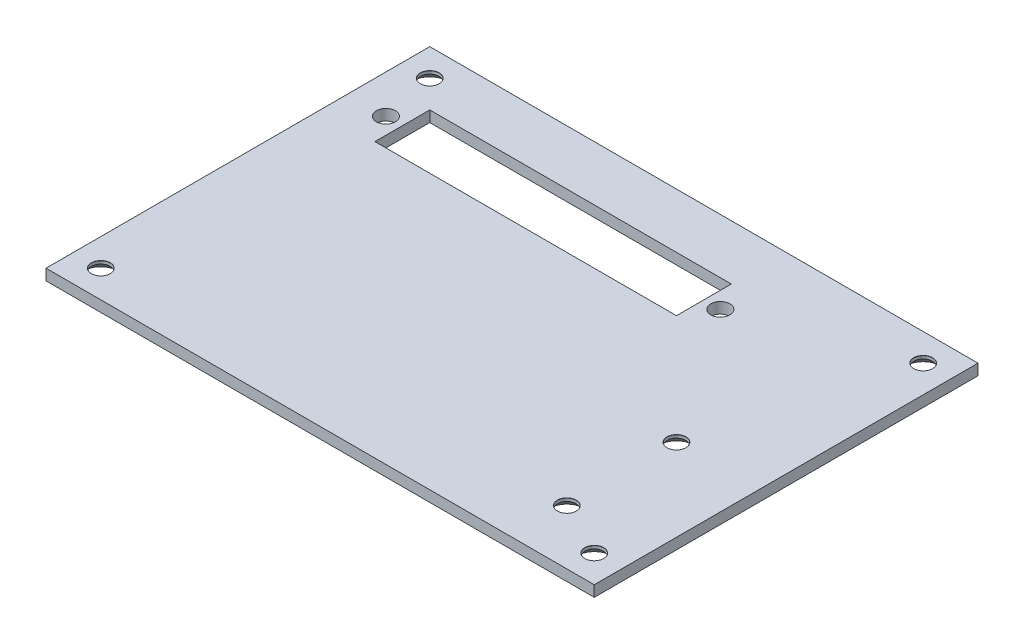
SolidWorks part; units mm, degrees
ref_plane "Ebene vorne" through (0, 0, 0) normal (0, 0, 1) x (1, 0, 0)
ref_plane "Ebene oben" through (0, 0, 0) normal (0, 1, 0) x (1, 0, 0)
ref_plane "Ebene rechts" through (0, 0, 0) normal (1, 0, 0) x (0, 0, -1)
sketch "Skizze1" plane through (0, 0, 0) normal (0, 1, 0) x (1, 0, 0)
  line L1 (0, 0) -> (100, 0)
  line L2 (0, 0) -> (0, 70)
  line L3 (0, 70) -> (100, 70)
  line L4 (100, 0) -> (100, 70)
  line L5 (10, 60) -> (65, 60)
  line L6 (10, 60) -> (10, 50)
  line L7 (10, 50) -> (65, 50)
  line L8 (65, 60) -> (65, 50)
  dimension "D1" = 100
  dimension "D2" = 70
  dimension "D3" = 10
  dimension "D4" = 55
  dimension "D5" = 10
  dimension "D6" = 10
extrude "Aufsatz-Linear austragen1" add sketch "Skizze1" along normal blind 2
hole_wizard "Ø3.5 (3.5) Durchmesser Bohrung1" positions "Skizze4" profile "Skizze5" hole size "Ø3.5" standard "DIN" end condition up to next
sketch "Skizze4" plane through (0, 2, 0) normal (0, 1, 0) x (1, 0, 0)
  line L1 (10, 60) -> (10, 50) construction
  line L2 (65, 50) -> (65, 60) construction
  line L3 (100, 70) -> (0, 70) construction
  point P0 (7, 55)
  point P2 (68, 55)
  dimension "D1" = 15
  dimension "D2" = 3
  dimension "D3" = 3
  dimension "D4" = 15
sketch "Skizze5" plane through (7, 2, -55) normal (1, 0, 0) x (0, 0, 1)
  line L0 (0, 0) -> (0, 2)
  line L1 (0, 2) -> (1.75, 2)
  line L2 (1.75, 2) -> (1.75, 0)
  line L5 (1.75, 0) -> (0, 0)
  line L11 (0, -6.35) -> (0, 107.95) construction
  dimension "Bohrerdurchmesser" = 3.5
  dimension "Bohrungstiefe" = 2
hole_wizard "Formsenkung für M3 Linsensenkschraube mit Schlitz1" positions "Skizze6" profile "Skizze7" countersink size "M3" standard "DIN" end condition up to next
sketch "Skizze6" plane through (0, 0, 0) normal (0, -1, 0) x (-1, 0, 0)
  line L0 (0, 0) -> (-100, 0) construction
  line L1 (0, 70) -> (0, 0) construction
  line L2 (-100, 0) -> (-100, 70) construction
  line L3 (-100, 70) -> (0, 70) construction
  point P0 (-5, 5)
  point P2 (-95, 5)
  point P4 (-95, 65)
  point P6 (-5, 65)
  dimension "D1" = 5
  dimension "D2" = 5
  dimension "D3" = 5
  dimension "D4" = 5
  dimension "D5" = 5
  dimension "D6" = 5
  dimension "D7" = 5
  dimension "D8" = 5
sketch "Skizze7" plane through (5, 0, -5) normal (1, 0, 0) x (0, 0, -1)
  line L0 (0, 0) -> (0, 2)
  line L1 (0, 2) -> (1.725, 2)
  line L2 (1.7, 1.975) -> (1.7, 1.45)
  line L3 (1.7, 1.45) -> (3.15, 0)
  line L5 (3.15, 0) -> (0, 0)
  line L6 (-1.7, 1.45) -> (-3.15, 0) construction
  line L7 (1.725, 2) -> (1.7, 1.975)
  line L8 (-1.725, 2) -> (-1.7, 1.975) construction
  line L11 (0, -6.35) -> (0, 107.95) construction
  dimension "Bohrerdurchmesser" = 3.4
  dimension "Bohrungstiefe" = 2
  dimension "Senkdurchmesser (Oben)" = 6.3
  dimension "Senkwinkel (Oben)" = 90
  dimension "Senkdurchmesser (Unten)" = 3.45
  dimension "Senkwinkel (Unten)" = 90
hole_wizard "Formsenkung für M3 Linsensenkschraube mit Schlitz2" positions "Skizze8" profile "Skizze9" countersink size "M3" standard "DIN" end condition up to next
sketch "Skizze8" plane through (0, 0, 0) normal (0, -1, 0) x (-1, 0, 0)
  line L0 (-100, 0) -> (-100, 70) construction
  line L1 (0, 0) -> (-100, 0) construction
  point P0 (-85, 10)
  point P2 (-85, 30)
  dimension "D1" = 15
  dimension "D2" = 20
  dimension "D3" = 15
  dimension "D4" = 10
sketch "Skizze9" plane through (85, 0, -10) normal (1, 0, 0) x (0, 0, -1)
  line L0 (0, 0) -> (0, 2)
  line L1 (0, 2) -> (1.725, 2)
  line L2 (1.7, 1.975) -> (1.7, 1.45)
  line L3 (1.7, 1.45) -> (3.15, 0)
  line L5 (3.15, 0) -> (0, 0)
  line L6 (-1.7, 1.45) -> (-3.15, 0) construction
  line L7 (1.725, 2) -> (1.7, 1.975)
  line L8 (-1.725, 2) -> (-1.7, 1.975) construction
  line L11 (0, -6.35) -> (0, 107.95) construction
  dimension "Bohrerdurchmesser" = 3.4
  dimension "Bohrungstiefe" = 2
  dimension "Senkdurchmesser (Oben)" = 6.3
  dimension "Senkwinkel (Oben)" = 90
  dimension "Senkdurchmesser (Unten)" = 3.45
  dimension "Senkwinkel (Unten)" = 90
